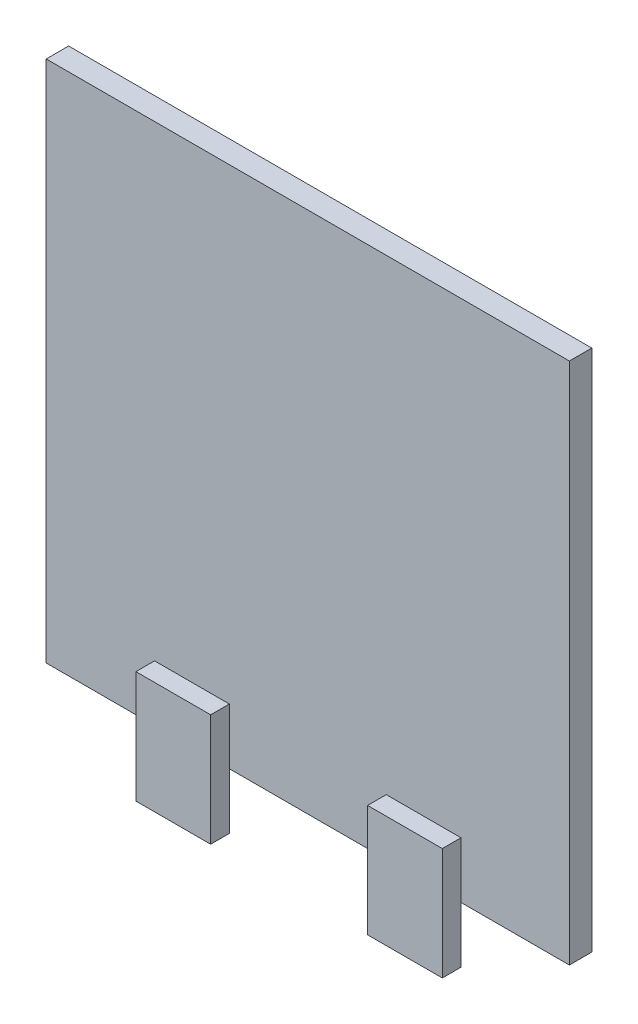
SolidWorks part; units mm, degrees
ref_plane "Front Plane" through (0, 0, 0) normal (0, 0, 1) x (1, 0, 0)
ref_plane "Top Plane" through (0, 0, 0) normal (0, 1, 0) x (1, 0, 0)
ref_plane "Right Plane" through (0, 0, 0) normal (1, 0, 0) x (0, 0, -1)
sketch "Sketch1" plane through (0, 0, 0) normal (0, 0, 1) x (1, 0, 0)
  line L1 (70, -70) -> (-70, -70)
  line L2 (70, -70) -> (70, 70)
  line L3 (70, 70) -> (-70, 70)
  line L4 (-70, -70) -> (-70, 70)
  point P6 (0, 0)
  point P7 (0, 0)
extrude "Boss-Extrude1" add sketch "Sketch1" along normal blind 6
sketch "Sketch2" plane through (0, 0, 6) normal (0, 0, 1) x (1, 0, 0)
  line L0 (-31, -80) -> (-31, -55) construction
  line L1 (-31, -55) -> (-41, -55) construction
  line L3 (-41, -55) -> (-21, -55)
  line L4 (-41, -55) -> (-41, -85)
  line L5 (-41, -85) -> (-21, -85)
  line L6 (-21, -55) -> (-21, -85)
  line L7 (0, -3.3) -> (0, 3.3) construction
  line L8 (31, -55) -> (41, -55) construction
  line L9 (31, -80) -> (31, -55) construction
  line L10 (21, -55) -> (21, -85)
  line L11 (41, -85) -> (21, -85)
  line L12 (41, -55) -> (41, -85)
  line L13 (41, -55) -> (21, -55)
extrude "Boss-Extrude2" add sketch "Sketch2" along normal blind 5
